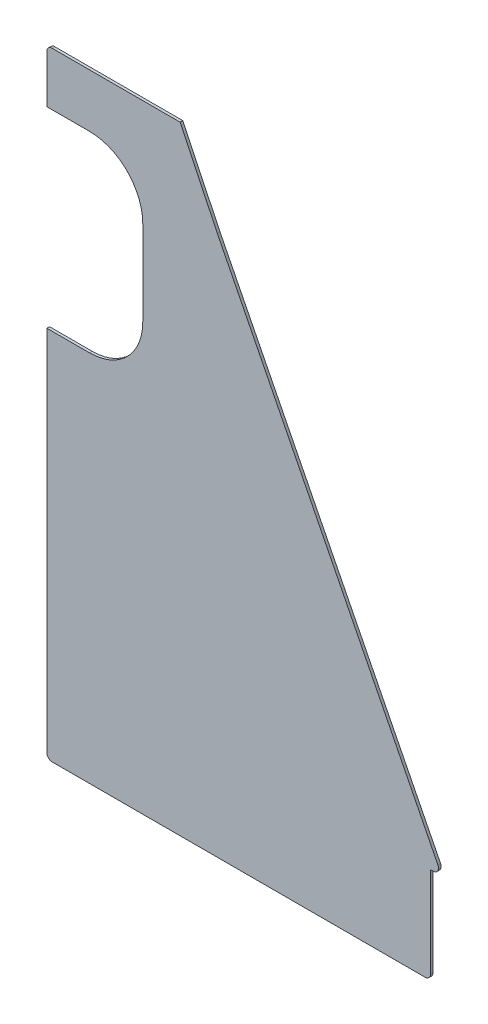
SolidWorks part; units mm, degrees
material "Thornel Mat VMA"
ref_plane "Front Plane" through (0, 0, 0) normal (0, 0, 1) x (1, 0, 0)
ref_plane "Top Plane" through (0, 0, 0) normal (0, 1, 0) x (1, 0, 0)
ref_plane "Right Plane" through (0, 0, 0) normal (1, 0, 0) x (0, 0, -1)
sketch "Sketch1" plane through (0, 0, 0) normal (0, 0, 1) x (1, 0, 0)
  line L1 (-360, -580) -> (360, -580)
  line L2 (-360, -580) -> (-360, 580)
  line L3 (-360, 580) -> (360, 580)
  line L4 (360, -580) -> (360, 580)
  line L5 (-360, -580) -> (360, 580) construction
  line L6 (-360, 580) -> (360, -580) construction
  point P0 (0, 0)
  dimension "D1" = 1160
  dimension "D2" = 720
extrude "Boss-Extrude1" add sketch "Sketch1" along normal blind 5
fillet "Fillet1" radius 10 4 edges at (-360, -580, 2.5) (360, -580, 2.5) (360, 580, 2.5) (-360, 580, 2.5)
sketch "Sketch2" plane through (0, 0, 0) normal (0, 0, -1) x (-1, 0, 0)
  line L0 (-360, -400) -> (110, 580)
  line L2 (-350, 580) -> (350, 580) construction
  line L3 (360, 570) -> (360, -570) construction
  line L4 (-360, -400) -> (-360, 580)
  line L5 (-360, 580) -> (110, 580)
  line L6 (350, -580) -> (-350, -580) construction
  line L7 (-360, -570) -> (-360, 570) construction
  dimension "D1" = 250
  dimension "D2" = 180
extrude "Cut-Extrude1" cut sketch "Sketch2" against normal through all
sketch "Sketch3" plane through (0, 0, 5) normal (0, 0, 1) x (1, 0, 0)
  line L0 (-360, 570) -> (-360, -570) construction
  line L1 (-540, 120) -> (-180, 120)
  line L2 (-540, 120) -> (-540, 480)
  line L3 (-540, 480) -> (-180, 480)
  line L4 (-180, 120) -> (-180, 480)
  line L5 (-540, 120) -> (-180, 480) construction
  line L6 (-540, 480) -> (-180, 120) construction
  line L8 (-350, -580) -> (350, -580) construction
  point P0 (-360, 300)
  dimension "D1" = 180
  dimension "D2" = 360
  dimension "D3" = 700
extrude "Cut-Extrude2" cut sketch "Sketch3" against normal through all
fillet "Fillet2" radius 100 2 edges at (-180, 120, 2.5) (-180, 480, 2.5)
sketch "Sketch4" plane through (0, 0, 0) normal (0, 0, -1) x (-1, 0, 0)
  line L0 (-360, -400) -> (-381.2992, -400)
  line L2 (-381.2992, -400) -> (39.8879, 433.8088)
  line L4 (-360, -400) -> (110, 580) construction
  line L5 (-360, -400) -> (39.8879, 433.8088)
  point P3 (0, 0)
  point P5 (0, 0)
  dimension "D1" = 63.2
  dimension "D2" = 21.2992
  dimension "D3" = 833.8088
extrude "Boss-Extrude2" add sketch "Sketch4" against normal up to surface (5 mm away) up to face at (-147.1893, 59.1378, 5)
fillet "Fillet3" radius 10 1 edges at (381.2992, -400, 2.5)
